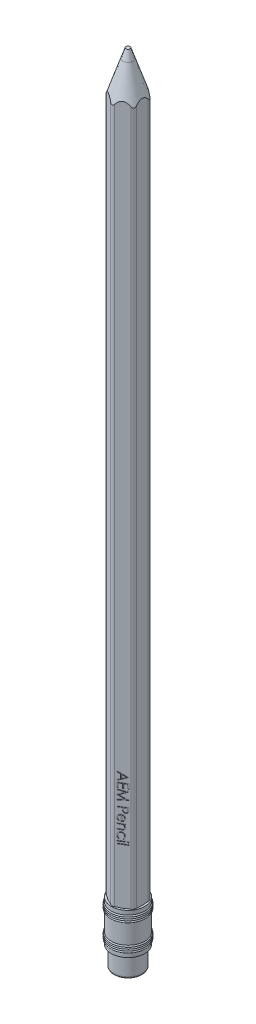
SolidWorks part; units mm, degrees
other "Text"
ref_plane "Front Plane" through (0, 0, 0) normal (0, 0, 1) x (1, 0, 0)
ref_plane "Top Plane" through (0, 0, 0) normal (0, 1, 0) x (1, 0, 0)
ref_plane "Right Plane" through (0, 0, 0) normal (1, 0, 0) x (0, 0, -1)
sketch "Sketch1" plane through (0, 0, 0) normal (0, 1, 0) x (1, 0, 0)
  circle A0 centre (0, 0) radius 1.25
  dimension "D1" = 2.5
extrude "Lead" add sketch "Sketch1" along normal blind 185
sketch "Sketch2" plane through (0, 185, 0) normal (0, 1, 0) x (1, 0, 0)
  line L1 (3.5, 2.0207) -> (0, 4.0415)
  line L2 (0, 4.0415) -> (-3.5, 2.0207)
  line L3 (-3.5, 2.0207) -> (-3.5, -2.0207)
  line L4 (-3.5, -2.0207) -> (0, -4.0415)
  line L5 (0, -4.0415) -> (3.5, -2.0207)
  line L6 (3.5, -2.0207) -> (3.5, 2.0207)
  circle A0 centre (0, 0) radius 3.5 construction
  circle A1 centre (0, 0) radius 1.25
  circle A2 centre (0, 0) radius 1.25 construction
  dimension "D1" = 7
extrude "Wooden Casing" add sketch "Sketch2" against normal up to surface (185 mm away) separate body up to face at (0, 0, 1.25)
sketch "Sketch3" plane through (0, 0, 0) normal (0, -1, 0) x (1, 0, 0)
  circle A0 centre (0, 0) radius 3.5
  dimension "D1" = 7
extrude "Eraser" add sketch "Sketch3" along normal blind 10 separate body
fillet "Fillet1" radius 0.5 1 edges at (0, -10, -3.5)
sketch "Sketch4" plane through (0, 0, 0) normal (0, 0, 1) x (1, 0, 0)
  line L0 (0, -10) -> (0, 0) construction
  line L1 (-3, -10) -> (3, -10) construction
  line L2 (3.5, 0) -> (-3.5, 0) construction
  line L3 (4.1, -5) -> (3.6, -5)
  line L4 (4.1, -5) -> (4.1, 5) construction
  line L5 (4.1, 5) -> (3.6, 5)
  line L6 (3.6, -5) -> (3.6, 5) construction
  line L7 (4.1, 0) -> (0, 0) construction
  line L8 (4.1, -2.4) -> (4.1, 2.4)
  line L9 (4.1, 4) -> (4.1, 5)
  line L10 (4.1, -5) -> (4.1, -4)
  line L11 (3.85, -5) -> (3.85, 5) construction
  line L12 (3.6, -5) -> (3.6, 5) construction
  line L13 (3.6, -5) -> (3.6, -4)
  line L14 (3.6, 4) -> (3.6, 5)
  line L15 (3.6, -2.4) -> (3.6, 2.4)
  arc A0 (4.1, 3.6) -> (4.1, 4) centre (4.1, 3.8) ccw
  arc A1 (4.1, 3.2) -> (4.1, 3.6) centre (4.1, 3.4) ccw
  arc A2 (4.1, 2.8) -> (4.1, 3.2) centre (4.1, 3) ccw
  arc A3 (4.1, 2.4) -> (4.1, 2.8) centre (4.1, 2.6) ccw
  arc A4 (4.1, -2.4) -> (4.1, -2.8) centre (4.1, -2.6) cw
  arc A5 (4.1, -2.8) -> (4.1, -3.2) centre (4.1, -3) cw
  arc A6 (4.1, -3.2) -> (4.1, -3.6) centre (4.1, -3.4) cw
  arc A7 (4.1, -3.6) -> (4.1, -4) centre (4.1, -3.8) cw
  arc A8 (3.6, -3.6) -> (3.6, -4) centre (3.6, -3.8) ccw
  arc A9 (3.6, -3.2) -> (3.6, -3.6) centre (3.6, -3.4) ccw
  arc A10 (3.6, -2.8) -> (3.6, -3.2) centre (3.6, -3) ccw
  arc A11 (3.6, -2.4) -> (3.6, -2.8) centre (3.6, -2.6) ccw
  arc A12 (3.6, 2.4) -> (3.6, 2.8) centre (3.6, 2.6) cw
  arc A13 (3.6, 2.8) -> (3.6, 3.2) centre (3.6, 3) cw
  arc A14 (3.6, 3.2) -> (3.6, 3.6) centre (3.6, 3.4) cw
  arc A15 (3.6, 3.6) -> (3.6, 4) centre (3.6, 3.8) cw
  dimension "D5" = 1
  dimension "D6" = 0.4
  dimension "D1" = 10
  dimension "D2" = 5
  dimension "D3" = 0.5
  dimension "D4" = 4.1
  dimension "D7" = 4
revolve "Ferrule" add sketch "Sketch4" angle 360 about L0
fillet "Fillet2" radius 1 6 edges at (0, 92.5, -4.0415) (-3.5, 92.5, -2.0207) (-3.5, 92.5, 2.0207) (0, 92.5, 4.0415) (3.5, 92.5, 2.0207) (3.5, 92.5, -2.0207)
sketch "Sketch6" plane through (1.75, 0, 3.0311) normal (0.5, 0, 0.866) x (0.866, 0, -0.5)
  line L0 (-1.0434, 34) -> (-1.0434, 4) construction
  line L1 (4.1, 4) -> (-4.1, 4) construction
  line L2 (-1.4434, 185) -> (-1.4434, 0) construction
  text T0 "AEM Pencil" font "Century Gothic" height in points 8
  dimension "D1" = 30
  dimension "D2" = 0.4
extrude "Text" cut sketch "Sketch6" against normal blind 0.1
sketch "Sketch7" plane through (0, 0, 0) normal (0, 0, 1) x (1, 0, 0)
  line L0 (0, 185) -> (0, 170) construction
  line L1 (1.25, 185) -> (-1.25, 185) construction
  line L2 (0.5, 185) -> (5.5, 185)
  line L3 (1.25, 185) -> (-1.25, 185) construction
  line L4 (5.5, 185) -> (5.5, 170)
  line L5 (5.5, 170) -> (0.5, 185)
  dimension "D1" = 15
  dimension "D2" = 5
  dimension "D3" = 0.5
  dimension "D4" = 15
revolve "Sharpening Cut" cut sketch "Sketch7" angle 360 about L0
